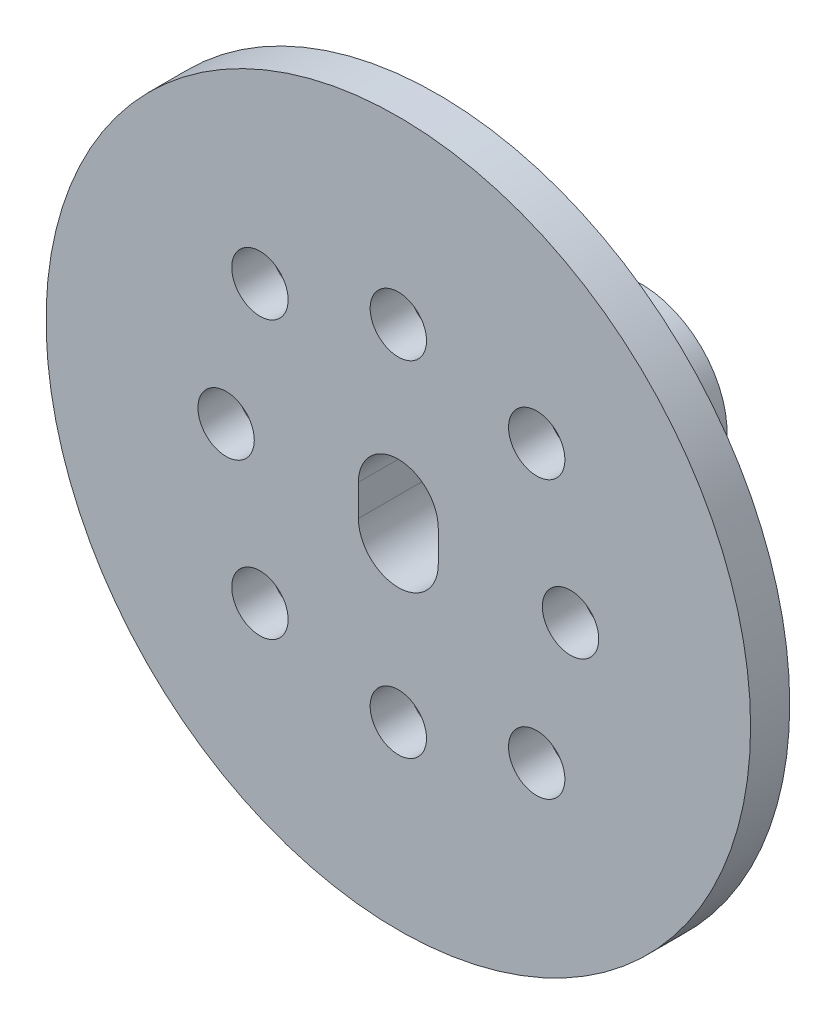
SolidWorks part; units mm, degrees
ref_plane "前视基准面" through (0, 0, 0) normal (0, 0, 1) x (1, 0, 0)
ref_plane "上视基准面" through (0, 0, 0) normal (0, 1, 0) x (1, 0, 0)
ref_plane "右视基准面" through (0, 0, 0) normal (1, 0, 0) x (0, 0, -1)
other "Configuration Table"
sketch "草图1" plane through (0, 0, 0) normal (0, 0, 1) x (1, 0, 0)
  circle A1 centre (0, 0) radius 22.5
  dimension "D2" = 45
extrude "凸台-拉伸1" add sketch "草图1" along normal blind 2.5
sketch "草图4" plane through (0, 0, 0) normal (0, 0, -1) x (-1, 0, 0)
  circle A0 centre (0, 0) radius 7.5
  dimension "D1" = 15
extrude "凸台-拉伸2" add sketch "草图4" along normal blind 4
sketch "草图5" plane through (0, 0, -4) normal (0, 0, -1) x (-1, 0, 0)
  line L0 (-0.0002, -0.9999) -> (-0.0002, 1.0001) construction
  line L1 (-2.5502, -0.9999) -> (-2.5502, 1.0001)
  line L2 (2.5498, -0.9999) -> (2.5498, 1.0001)
  circle A0 centre (-0.0002, 0.0001) radius 3.55
  circle A1 centre (-0.0002, 0.0001) radius 7.5
  arc A2 (-2.5502, -0.9999) -> (2.5498, -0.9999) centre (-0.0002, -0.9999) ccw
  arc A3 (2.5498, 1.0001) -> (-2.5502, 1.0001) centre (-0.0002, 1.0001) ccw
  point P6 (-0.0002, 0.0001)
  circle M5 centre (0, 0) radius 7.5
  dimension "D1" = 7.1
  dimension "D2" = 5.1
extrude "凸台-拉伸3" add sketch "草图5" along normal blind 9 contours A0 M5 | A3 A0 A2 L1 | A3 L2 A2 A0
sketch "草图6" plane through (0, 0, 2.5) normal (0, 0, 1) x (1, 0, 0)
  line L0 (0, 0) -> (-21.0228, 21.0228) construction
  line L1 (0, 0) -> (-37.0664, 0) construction
  circle A0 centre (0, 0) radius 11 construction
  circle A1 centre (0, 0) radius 12.5 construction
  circle A2 centre (0, 11) radius 1.8
  circle A4 centre (-8.8388, 8.8388) radius 1.8
  circle A5 centre (8.8388, 8.8388) radius 1.8
  circle A6 centre (8.8388, -8.8388) radius 1.8
  circle A7 centre (-8.8388, -8.8388) radius 1.8
  circle A8 centre (11, 0) radius 1.8
  circle A9 centre (0, -11) radius 1.8
  circle A10 centre (-11, 0) radius 1.8
  point P19 (0, 0)
  point P26 (0, 0)
  dimension "D1" = 25
  dimension "D2" = 22
  dimension "D3" = 3.6
  dimension "D5" = 3.6
  dimension "D6" = 4
  dimension "D7" = 4
  dimension "D4" = 45
extrude "切除-拉伸2" cut sketch "草图6" against normal blind 6
fillet "圆角1" radius 0.5 4 edges at (-2.5498, 0.0001, -13) (0.0002, -3.5499, -13) (2.5502, 0.0001, -13) (0.0002, 3.5501, -13)
sketch "草图7" plane through (0, 0, -4) normal (0, 0, -1) x (-1, 0, 0)
  line L2 (-2.5502, 1.0001) -> (-2.5502, -0.9999)
  line L3 (2.5498, -0.9999) -> (2.5498, 1.0001)
  line L4 (-2.5502, 1.0001) -> (-2.5502, -0.9999)
  line L5 (2.5498, -0.9999) -> (2.5498, 1.0001)
  arc A2 (-2.5502, -0.9999) -> (2.5498, -0.9999) centre (-0.0002, -0.9999) ccw
  arc A3 (2.5498, 1.0001) -> (-2.5502, 1.0001) centre (-0.0002, 1.0001) ccw
  arc A4 (-2.5502, -0.9999) -> (2.5498, -0.9999) centre (-0.0002, -0.9999) ccw
  arc A5 (2.5498, 1.0001) -> (-2.5502, 1.0001) centre (-0.0002, 1.0001) ccw
  dimension "D1" = 0
extrude "切除-拉伸3" cut sketch "草图7" against normal through all
sketch "草图8" plane through (0, 0, -13) normal (0, 0, -1) x (-1, 0, 0)
  circle A0 centre (0, 0) radius 7.5003
  circle A1 centre (0, 0) radius 5.5
  circle A2 centre (0, 0) radius 22.5 construction
  dimension "D1" = 11
extrude "切除-拉伸4" cut sketch "草图8" against normal blind 13
